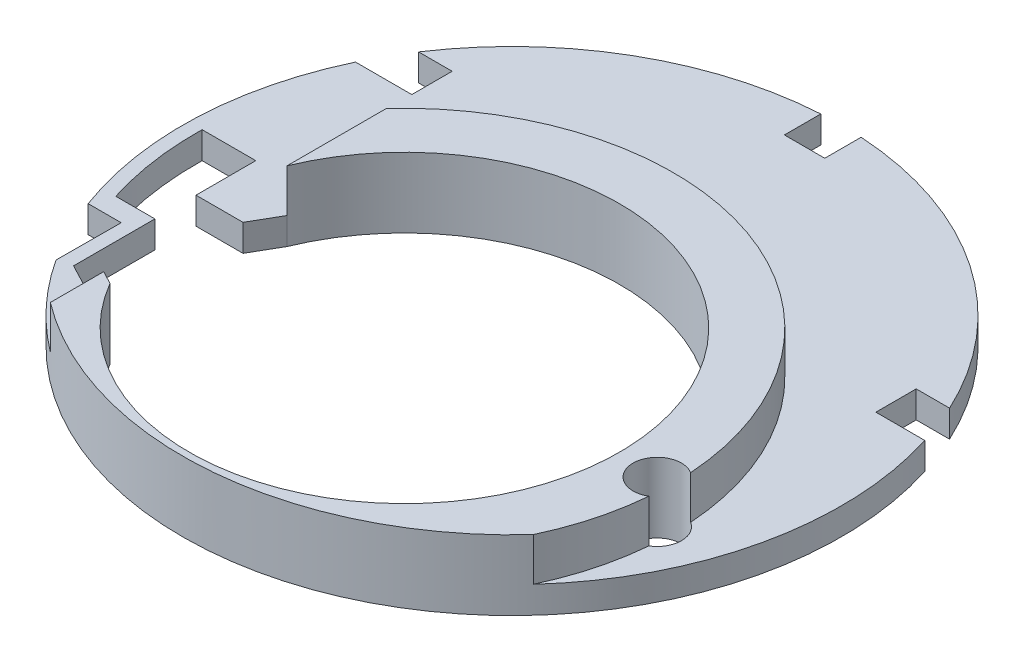
SolidWorks part; units mm, degrees
ref_plane "Front Plane" through (0, 0, 0) normal (0, 0, 1) x (1, 0, 0)
ref_plane "Top Plane" through (0, 0, 0) normal (0, 1, 0) x (1, 0, 0)
ref_plane "Right Plane" through (0, 0, 0) normal (1, 0, 0) x (0, 0, -1)
sketch "Sketch1" plane through (0, 0, 0) normal (0, 1, 0) x (1, 0, 0)
  line L5 (-0.75, 12.227) -> (-0.75, 10.875)
  line L6 (0.75, 12.227) -> (0.75, 10.875)
  line L7 (0.75, 10.875) -> (-0.75, 10.875)
  line L13 (-11.068, 5.25) -> (-8.975, 5.25)
  line L14 (-8.975, 5.25) -> (-8.975, 6.75)
  line L15 (-8.975, 6.75) -> (-10.2225, 6.75)
  line L20 (11.1149, 5.15) -> (9.875, 5.15)
  line L21 (9.875, 5.15) -> (9.875, 3.65)
  line L22 (9.875, 3.65) -> (11.6936, 3.65)
  line L23 (-11.7455, -4.2772) -> (-10.2515, -4.2772)
  line L27 (-10.2515, -4.2772) -> (-10.262, -6.6899)
  arc A0 (-0.75, 12.227) -> (-10.2225, 6.75) centre (0, 0) ccw
  arc A1 (-11.068, 5.25) -> (-11.479, -4.2772) centre (0, 0) ccw
  arc A4 (-10.262, -6.6899) -> (11.6936, 3.65) centre (0, 0) ccw
  arc A5 (11.1149, 5.15) -> (0.75, 12.227) centre (0, 0) ccw
extrude "Boss-Extrude1" add sketch "Sketch1" along normal blind 1
sketch "Sketch3" plane through (0, 1, 0) normal (0, 1, 0) x (1, 0, 0)
  line L0 (-7.4007, -0.962) -> (-7.4007, 2.7253)
  line L1 (-7.4007, -7.038) -> (-7.4007, -9.7618)
  circle A0 centre (0, 0) radius 12.25
  circle A1 centre (0, -4) radius 8
  circle A2 centre (0, -4) radius 10
extrude "Boss-Extrude2" add sketch "Sketch3" along normal blind 1.6
sketch "Sketch2" plane through (0, 1, 0) normal (0, 1, 0) x (1, 0, 0)
  line L0 (-9.748, -2) -> (-9.748, 0.2228)
  line L1 (-9.748, 0.2228) -> (-11.7479, 0.2228)
  line L2 (-9.748, -3.5272) -> (-9.748, -6.5515)
  line L3 (-8, -2) -> (-7.4007, -0.962)
  line L4 (-8, -2) -> (-8.5, -2)
  line L10 (-8.5, -2) -> (-9.748, -2)
  line L11 (-9.748, -6.5515) -> (-6.9064, -8.0376)
  line L16 (-11.2081, -3.5272) -> (-9.748, -3.5272)
  arc A0 (-6.9064, -8.0376) -> (-7.4007, -0.962) centre (0, -4) ccw
  arc A1 (-11.7429, 0.2228) -> (-3.3965, -11.2432) centre (0, 0) ccw
  circle A2 centre (9.5, -4.1) radius 0.9
  arc A5 (-11.7479, 0.2228) -> (-11.2081, -3.5272) centre (0, 0) ccw
  point P12 (-8, -4)
extrude "Cut-Extrude1" cut sketch "Sketch2" against normal through all both and the other way through all
